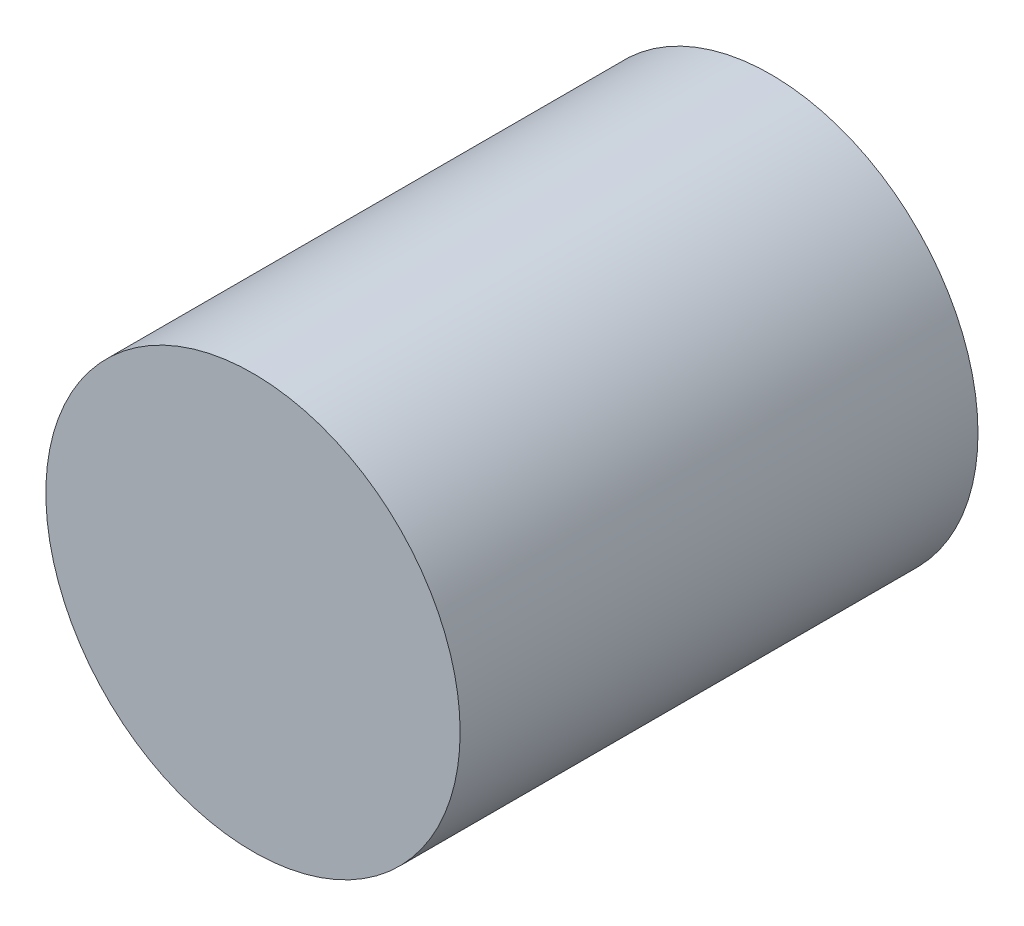
SolidWorks part; units mm, degrees
ref_plane "Plano frontal" through (0, 0, 0) normal (0, 0, 1) x (1, 0, 0)
ref_plane "Plano superior" through (0, 0, 0) normal (0, 1, 0) x (1, 0, 0)
ref_plane "Plano direito" through (0, 0, 0) normal (1, 0, 0) x (0, 0, -1)
sketch "Esboço1" plane through (0, 0, 0) normal (0, 0, 1) x (1, 0, 0)
  circle A0 centre (0, 0) radius 10
extrude "Ressalto-extrusão1" add sketch "Esboço1" along normal blind 25
